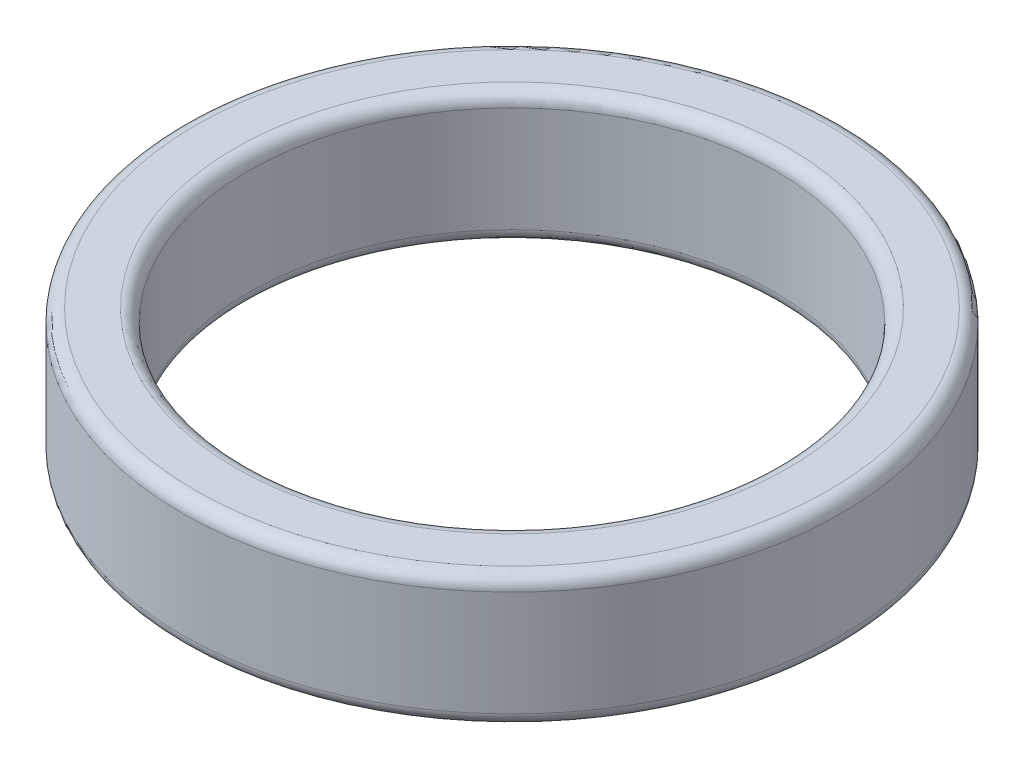
SolidWorks part; units mm, degrees
ref_plane "Plan de face" through (0, 0, 0) normal (0, 0, 1) x (1, 0, 0)
ref_plane "Plan de dessus" through (0, 0, 0) normal (0, 1, 0) x (1, 0, 0)
ref_plane "Plan de droite" through (0, 0, 0) normal (1, 0, 0) x (0, 0, -1)
sketch "Esquisse1" plane through (0, 0, 0) normal (0, 1, 0) x (1, 0, 0)
  circle A0 centre (0, 0) radius 12.5
  circle A1 centre (0, 0) radius 10
  dimension "D1" = 20
  dimension "D2" = 25
extrude "Boss.-Extru.1" add sketch "Esquisse1" along normal blind 5
fillet "Congé1" radius 0.5 4 edges at (0, 0, 12.5) (0, 5, 12.5) (0, 0, 10) (0, 5, 10)
